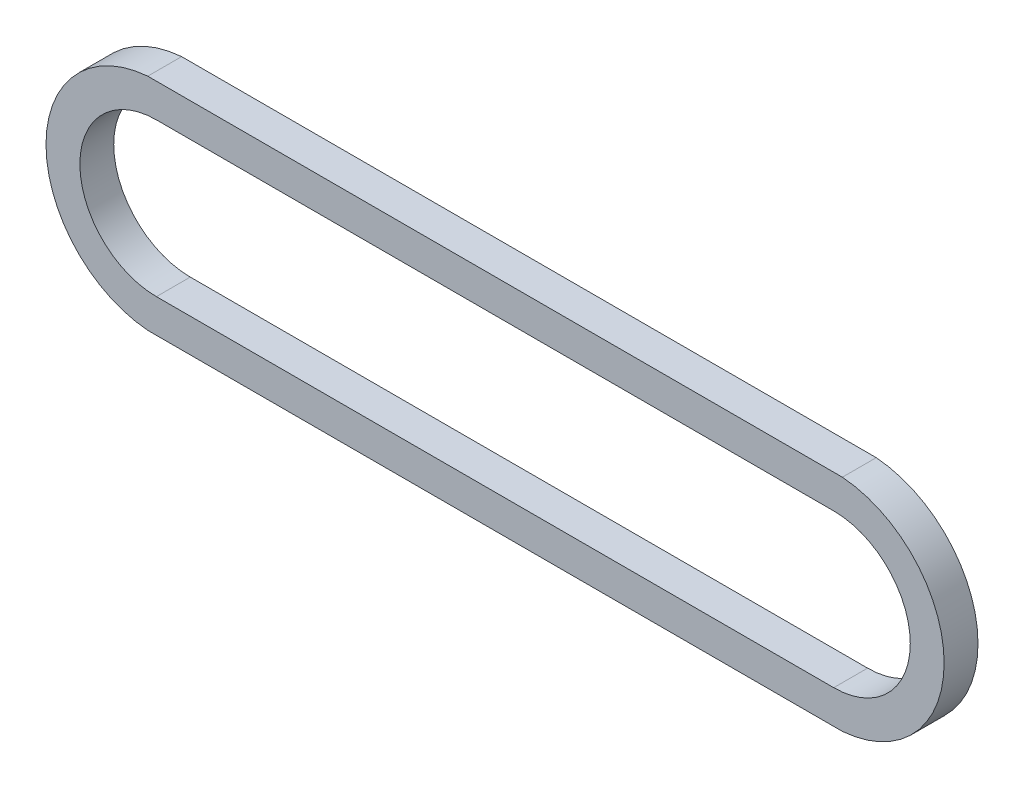
SolidWorks part; units mm, degrees
ref_plane "Front" through (0, 0, 0) normal (0, 0, 1) x (1, 0, 0)
ref_plane "Top" through (0, 0, 0) normal (0, 1, 0) x (1, 0, 0)
ref_plane "Right" through (0, 0, 0) normal (1, 0, 0) x (0, 0, -1)
sketch "Sketch1" plane through (0, 0, 0) normal (0, 0, 1) x (1, 0, 0)
  line L1 (84.201, 20.6375) -> (-84.201, 20.6375)
  line L2 (84.201, 20.6375) -> (84.201, -20.6375)
  line L3 (84.201, -20.6375) -> (-84.201, -20.6375)
  line L4 (-84.201, 20.6375) -> (-84.201, -20.6375)
  line L5 (84.201, 20.6375) -> (-84.201, -20.6375) construction
  line L6 (84.201, -20.6375) -> (-84.201, 20.6375) construction
  point P0 (0, 0)
  dimension "D1" = 168.402
  dimension "D2" = 41.275
extrude "Boss-Extrude1" add sketch "Sketch1" along normal blind 6.35
sketch "Sketch2" plane through (0, 0, 6.35) normal (0, 0, 1) x (1, 0, 0)
  line L0 (63.5, 0) -> (-63.5, 0) construction
  line L1 (63.5, -14.351) -> (-63.5, -14.351)
  line L2 (63.5, 14.351) -> (-63.5, 14.351)
  arc A0 (63.5, -14.351) -> (63.5, 14.351) centre (63.5, 0) ccw
  arc A1 (-63.5, 14.351) -> (-63.5, -14.351) centre (-63.5, 0) ccw
  point P2 (0, 0)
  dimension "D1" = 127
  dimension "D2" = 28.702
extrude "Cut-Extrude1" cut sketch "Sketch2" against normal through all
sketch "Sketch5" plane through (0, 0, 6.35) normal (0, 0, 1) x (1, 0, 0)
  line L0 (-63.5, 20.701) -> (63.5, 20.701)
  line L1 (-63.5, -20.701) -> (63.5, -20.701)
  arc A0 (-63.5, 14.351) -> (-63.5, -14.351) centre (-63.5, 0) ccw
  arc A1 (-63.5, 20.701) -> (-63.5, -20.701) centre (-63.5, 0) ccw
  arc A2 (63.5, 14.351) -> (63.5, -14.351) centre (63.5, 0) cw
  arc A3 (63.5, -14.351) -> (63.5, 14.351) centre (63.5, 0) ccw construction
  arc A4 (63.5, 20.701) -> (63.5, -20.701) centre (63.5, 0) cw
  line M5 (-84.201, 20.6375) -> (-84.201, -20.6375)
  line M6 (-84.201, -20.6375) -> (84.201, -20.6375)
  line M7 (84.201, -20.6375) -> (84.201, 20.6375)
  line M8 (84.201, 20.6375) -> (-84.201, 20.6375)
  dimension "D1" = 6.35
  dimension "D2" = 6.35
extrude "Cut-Extrude2" cut sketch "Sketch5" against normal through all contours A1 M8 M5 | A1 M5 M6 | A4 M8 M7 | A4 M7 M6
